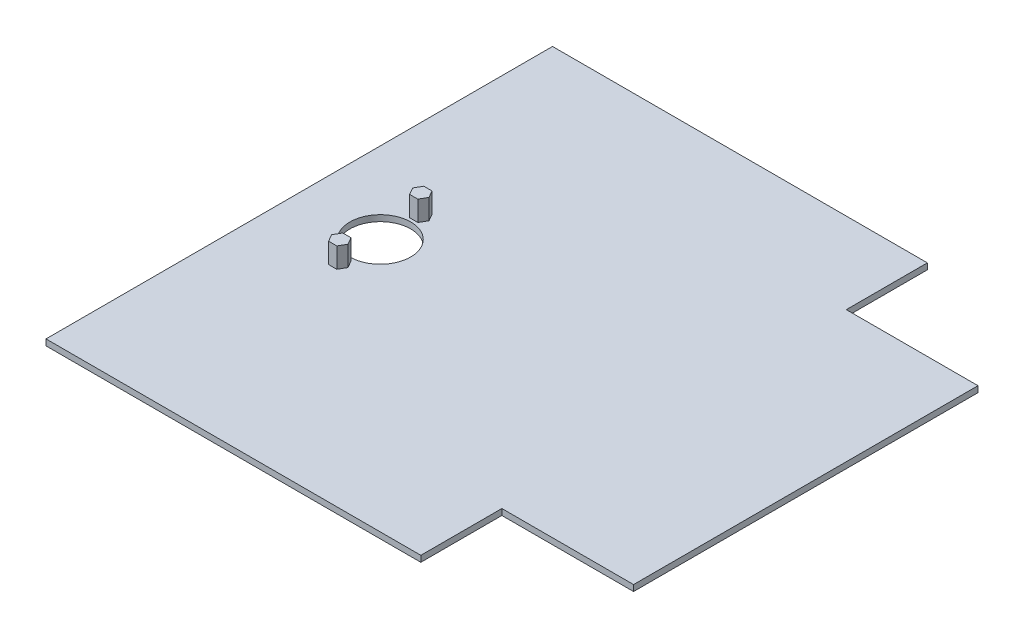
SolidWorks part; units mm, degrees
ref_plane "Front Plane" through (0, 0, 0) normal (0, 0, 1) x (1, 0, 0)
ref_plane "Top Plane" through (0, 0, 0) normal (0, 1, 0) x (1, 0, 0)
ref_plane "Right Plane" through (0, 0, 0) normal (1, 0, 0) x (0, 0, -1)
sketch "Sketch1" plane through (0, 0, 0) normal (0, 1, 0) x (1, 0, 0)
  line L1 (0, 0) -> (185, 0)
  line L2 (0, 0) -> (0, 250)
  line L3 (0, 250) -> (185, 250)
  line L4 (250, 40) -> (250, 210)
  line L6 (185, 0) -> (185, 40)
  line L7 (185, 40) -> (250, 40)
  line L11 (250, 210) -> (185, 210)
  line L12 (185, 250) -> (185, 210)
  circle A0 centre (40, 125) radius 15
  point P11 (0, 125)
  point P21 (0, 0)
  dimension "D7" = 30
  dimension "D1" = 0
  dimension "D2" = 250
  dimension "D3" = 65
  dimension "D4" = 40
  dimension "D5" = 65
  dimension "D6" = 40
  dimension "D8" = 40
extrude "Boss-Extrude2" add sketch "Sketch1" along normal blind 3
sketch "Sketch2" plane through (0, 3, 0) normal (0, 1, 0) x (1, 0, 0)
  line L0 (0, 250) -> (0, 0) construction
  line L1 (44.0415, 145) -> (42.0207, 148.5)
  line L2 (42.0207, 148.5) -> (37.9793, 148.5)
  line L3 (37.9793, 148.5) -> (35.9585, 145)
  line L4 (35.9585, 145) -> (37.9793, 141.5)
  line L5 (37.9793, 141.5) -> (42.0207, 141.5)
  line L6 (42.0207, 141.5) -> (44.0415, 145)
  line L7 (44.0415, 105) -> (42.0207, 108.5)
  line L8 (42.0207, 108.5) -> (37.9793, 108.5)
  line L9 (37.9793, 108.5) -> (35.9585, 105)
  line L10 (35.9585, 105) -> (37.9793, 101.5)
  line L11 (37.9793, 101.5) -> (42.0207, 101.5)
  line L12 (42.0207, 101.5) -> (44.0415, 105)
  circle A0 centre (40, 145) radius 3.5 construction
  circle A1 centre (40, 105) radius 3.5 construction
  point P18 (0, 125)
  dimension "D1" = 40
  dimension "D2" = 20
  dimension "D3" = 7
  dimension "D4" = 7
  dimension "D5" = 40
extrude "Boss-Extrude3" add sketch "Sketch2" along normal blind 10
